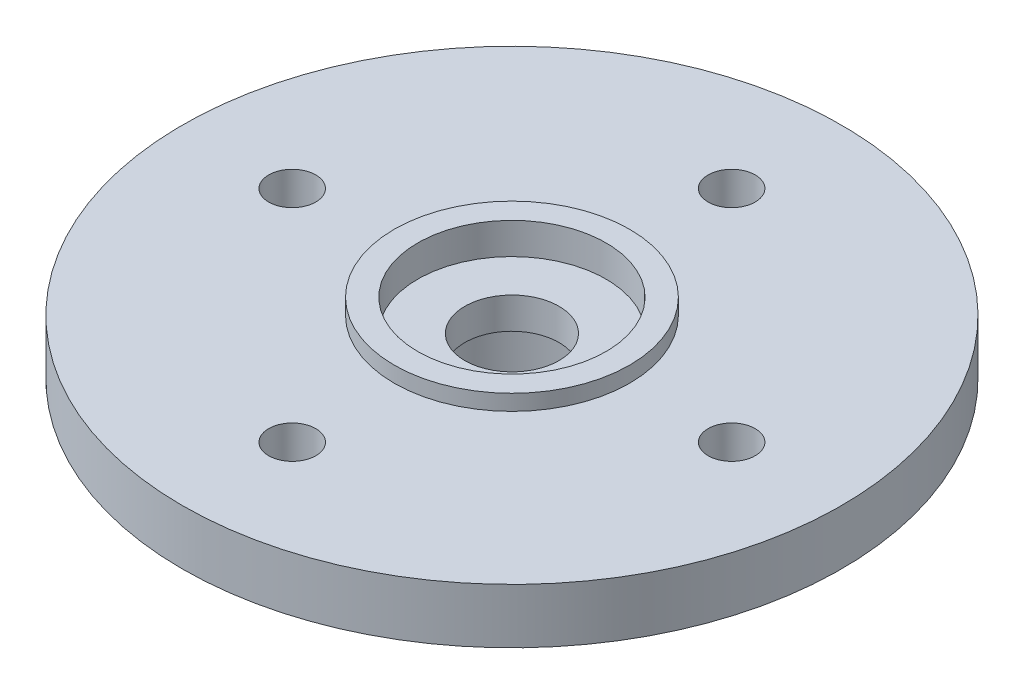
SolidWorks part; units mm, degrees
ref_plane "Plan de face" through (0, 0, 0) normal (0, 0, 1) x (1, 0, 0)
ref_plane "Plan de dessus" through (0, 0, 0) normal (0, 1, 0) x (1, 0, 0)
ref_plane "Plan de droite" through (0, 0, 0) normal (1, 0, 0) x (0, 0, -1)
ref_plane "Plan1" through (0, 0, 0) normal (0, 0, -1) x (-1, 0, 0)
sketch "Esquisse1" plane through (0, 0, 0) normal (0, 0, -1) x (-1, 0, 0)
  line L0 (-10.5, -1.75) -> (0, -1.75)
  line L1 (0, -1.75) -> (0, 0)
  line L2 (0, 0) -> (-10.5, 0)
  line L3 (-10.5, 0) -> (-10.5, -1.75)
  line L4 (0, -1.75) -> (0, 0) construction
  line L5 (0, 0) -> (0, -6.7959) construction
  dimension "D1" = 21
revolve "Révolution1" add sketch "Esquisse1" angle 360 about L4
sketch "Esquisse2" plane through (0, -1.75, 0) normal (0, -1, 0) x (1, 0, 0)
  circle A0 centre (0, 0) radius 4.45
extrude "Boss.-Extru.1" add sketch "Esquisse2" along normal blind 2.5
sketch "Esquisse3" plane through (0, 0, 0) normal (0, 1, 0) x (-1, 0, 0)
  circle A0 centre (0, 0) radius 3.75
extrude "Boss.-Extru.2" add sketch "Esquisse3" along normal blind 0.5
sketch "Esquisse4" plane through (0, 0, 0) normal (0, 0, -1) x (-1, 0, 0)
  line L0 (-3, -4.5) -> (0, -4.5)
  line L1 (0, -4.5) -> (0, 0.5)
  line L2 (0, 0.5) -> (-3, 0.5)
  line L3 (-3, 0.5) -> (-3, -0.5)
  line L4 (-3, -0.5) -> (-1.5006, -0.5)
  line L5 (-1.5006, -0.5) -> (-1.5006, -1.5)
  line L6 (-1.5006, -1.5) -> (-3, -1.5)
  line L7 (-3, -1.5) -> (-3, -4.5)
  line L8 (0, -4.5) -> (0, 0.5) construction
revolve "Enlèvement de matière-Révolution1" cut sketch "Esquisse4" angle 360 about L8
hole_wizard "Diamètre du perçage Ø1.5 (1.5)1" positions "Esquisse6" profile "Esquisse5" hole size "Ø1.5" standard "Ansi Metric"
sketch "Esquisse6" plane through (0, -1.75, 0) normal (0, -1, 0) x (-1, 0, 0)
  point P17 (-7, 0)
  point P34 (0, 7)
  point P38 (7, 0)
  point P42 (0, -7)
  point P43 (0, 0)
  point P44 (2.5882, 9.6593)
  point P45 (-2.5882, 9.6593)
  point P46 (0, 10)
  point P47 (-2.5882, -9.6593)
  point P48 (2.5882, -9.6593)
  point P49 (0, -10)
  dimension "D1" = 4
  dimension "D2" = 7
sketch "Esquisse5" plane through (7, -1.75, 0) normal (1, 0, 0) x (0, 0, -1)
  line L0 (0, 0) -> (0, 2.25)
  line L1 (0, 2.25) -> (0.75, 2.25)
  line L2 (0.75, 2.25) -> (0.75, 0)
  line L5 (0.75, 0) -> (0, 0)
  line L11 (0, -6.35) -> (0, 107.95) construction
  dimension "Diamètre du perçage jusqu'au prochain" = 1.5
  dimension "Profondeur du perçage jusqu'au prochain" = 2.25
